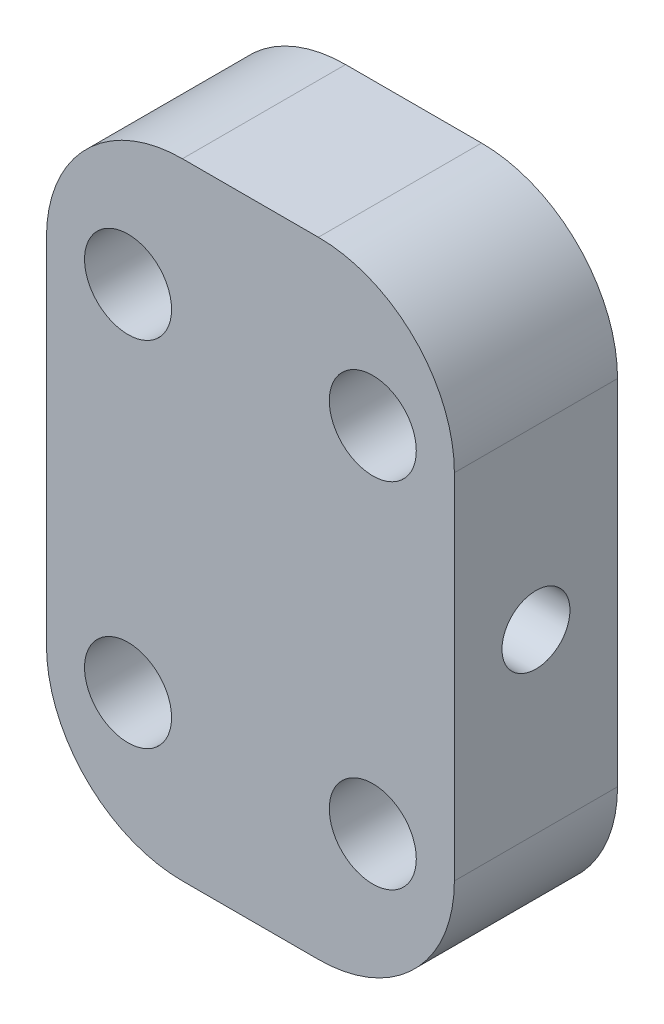
SolidWorks part; units mm, degrees
material "3.1325 (EN-AW 2017A)"
ref_plane "正面" through (0, 0, 0) normal (0, 0, 1) x (1, 0, 0)
ref_plane "平面" through (0, 0, 0) normal (0, 1, 0) x (1, 0, 0)
ref_plane "右側面" through (0, 0, 0) normal (1, 0, 0) x (0, 0, -1)
sketch "ｽｹｯﾁ1" plane through (0, 0, 0) normal (0, 0, 1) x (1, 0, 0)
  line L0 (0, 11.5) -> (0, 0) construction
  line L1 (-7.5, 11.5) -> (7.5, 11.5)
  line L2 (-7.5, 11.5) -> (-7.5, -11.5)
  line L3 (-7.5, -11.5) -> (7.5, -11.5)
  line L4 (7.5, 11.5) -> (7.5, -11.5)
  line L5 (-7.5, 11.5) -> (7.5, -11.5) construction
  line L6 (-7.5, -11.5) -> (7.5, 11.5) construction
  line L7 (0, 0) -> (7.5, 0) construction
  point P0 (0, 0)
  point P8 (4.5, 6.5)
  point P10 (-4.5, 6.5)
  point P11 (-4.5, -6.5)
  point P12 (4.5, -6.5)
  dimension "D1" = 15
  dimension "D2" = 23
  dimension "D3" = 9
  dimension "D4" = 13
extrude "ﾎﾞｽ - 押し出し1" add sketch "ｽｹｯﾁ1" along normal mid plane 6
fillet "ﾌｨﾚｯﾄ1" radius 5 4 edges at (7.5, 11.5, 0) (7.5, -11.5, 0) (-7.5, -11.5, 0) (-7.5, 11.5, 0)
hole_wizard "M3 すきま穴1" positions "3Dｽｹｯﾁ1" profile "ｽｹｯﾁ2" hole size "M3" standard "JIS" end condition through all
sketch3d "3Dｽｹｯﾁ1"
  point P0 (-4.5, 6.5, 3)
  point P2 (4.5, 6.5, 3)
  point P4 (4.5, -6.5, 3)
  point P6 (-4.5, -6.5, 3)
sketch "ｽｹｯﾁ2" plane through (-4.5, 6.5, 3) normal (1, 0, 0) x (0, -1, 0)
  line L0 (0, 0) -> (0, 6)
  line L1 (0, 6) -> (1.6, 6)
  line L2 (1.6, 6) -> (1.6, 0)
  line L5 (1.6, 0) -> (0, 0)
  line L11 (0, -6.35) -> (0, 107.95) construction
  dimension "通し穴の直径" = 3.2
  dimension "通し穴の深さ" = 6
hole_wizard "M3x0.5 ねじ穴1" positions "3Dｽｹｯﾁ2" profile "ｽｹｯﾁ3" tap size "M3x0.5" standard "JIS" end condition through all
sketch3d "3Dｽｹｯﾁ2"
  point P0 (7.5, 0, 0)
sketch "ｽｹｯﾁ3" plane through (7.5, 0, 0) normal (0, 1, 0) x (0, 0, -1)
  line L0 (0, 0) -> (0, 15)
  line L1 (0, 15) -> (1.25, 15)
  line L2 (1.25, 15) -> (1.25, 0)
  line L5 (1.25, 0) -> (0, 0)
  line L11 (0, -6.35) -> (0, 107.95) construction
  dimension "ねじ山の主要直径" = 2.5
  dimension "次ｻｰﾌｪｽまでのねじ下穴ﾄﾞﾘﾙの深さ" = 15
equation "\"ミル径\"= 1"
equation "\"コーナR面取り\"= 5"
equation "\"D1@ﾌｨﾚｯﾄ1\"=\"コーナR面取り\""
